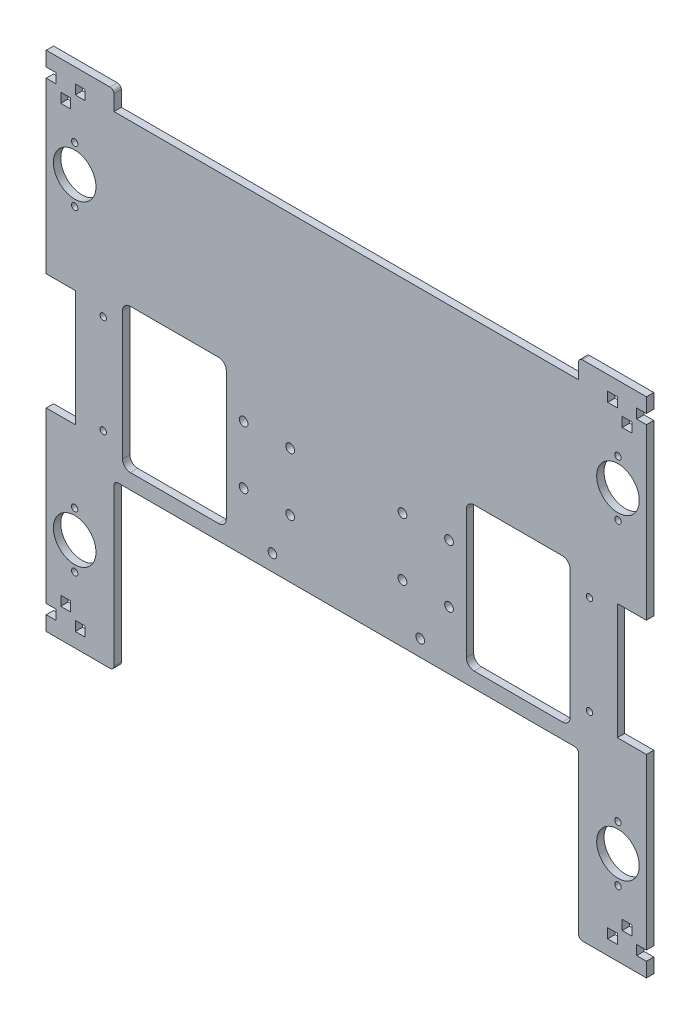
SolidWorks part; units mm, degrees
ref_plane "Front Plane" through (0, 0, 0) normal (0, 0, 1) x (1, 0, 0)
ref_plane "Top Plane" through (0, 0, 0) normal (0, 1, 0) x (1, 0, 0)
ref_plane "Right Plane" through (0, 0, 0) normal (1, 0, 0) x (0, 0, -1)
ref_plane "Plane1" through (0, 150, 0) normal (0, 1, 0) x (1, 0, 0)
ref_plane "Plane2" through (0, -150, 0) normal (0, 1, 0) x (1, 0, 0)
ref_plane "Plane3" through (150, 0, 0) normal (1, 0, 0) x (0, 0, -1)
ref_plane "Plane4" through (-150, 0, 0) normal (1, 0, 0) x (0, 0, -1)
sketch "Sketch2" plane through (0, 0, 0) normal (0, 0, 1) x (1, 0, 0)
  line L0 (0, -10.2) -> (0, 50.0764) construction
  line L5 (-53.06, 39.945) -> (-53.06, 10.055) construction
  line L23 (-155, 155) -> (-122, 155)
  line L24 (139.6652, 116) -> (168.3348, 116) construction
  line L31 (-155, -105) -> (-122, -105)
  line L40 (-152.1866, -81.0661) -> (-123.5266, -81.0661) construction
  line L42 (-120, 153) -> (-120, 145.0725)
  line L43 (-120, 145.0725) -> (120, 145.0725)
  line L47 (-66, 62.1714) -> (-111.5977, 62.1714)
  line L48 (66, 62.1714) -> (111.5977, 62.1714)
  line L49 (62, 58.1714) -> (62, -8.1714)
  line L50 (66, -12.1714) -> (111.5977, -12.1714)
  line L51 (115.5977, 58.1714) -> (115.5977, -8.1714)
  line L52 (62, 62.1714) -> (115.5977, -12.1714) construction
  line L53 (62, -12.1714) -> (115.5977, 62.1714) construction
  line L54 (-62, 58.1714) -> (-62, -8.1714)
  line L55 (-66, -12.1714) -> (-111.5977, -12.1714)
  line L56 (-115.5977, 58.1714) -> (-115.5977, -8.1714)
  line L57 (177.1787, -66.0847) -> (177.1787, 11.9153) construction
  line L66 (-155, -97.5) -> (-155, -105)
  line L70 (-125.5977, 50.5) -> (-125.5977, -0.5) construction
  line L73 (-155, 155) -> (-155, 147.5)
  line L74 (162.5, 25) -> (139.6652, 25) construction
  line L75 (-120, -103) -> (-120, -22)
  line L76 (-118, -20) -> (118, -20)
  line L79 (-155, -5) -> (-155, -92.5)
  line L80 (-155, -5) -> (-140, -5)
  line L82 (-155, 55) -> (-140, 55)
  line L83 (-140, -5) -> (-140, 55)
  line L84 (-145.4163, 25) -> (-140, 55) construction
  line L85 (-145.4163, 25) -> (-140, -5) construction
  line L88 (145.4163, 25) -> (140, -5) construction
  line L89 (145.4163, 25) -> (140, 55) construction
  line L90 (125.5977, 50.5) -> (125.5977, -0.5) construction
  line L91 (140, -5) -> (140, 55)
  line L92 (155, 55) -> (140, 55)
  line L93 (155, -5) -> (140, -5)
  line L94 (155, -5) -> (155, -92.5)
  line L95 (155, 155) -> (155, 147.5)
  line L96 (120, -103) -> (120, -22)
  line L97 (155, -105) -> (122, -105)
  line L98 (155, 155) -> (122, 155)
  line L99 (120, 153) -> (120, 145.0725)
  line L100 (-142.5, -90) -> (-147.5, -90)
  line L101 (-142.5, -90) -> (-142.5, -85)
  line L102 (-142.5, -85) -> (-147.5, -85)
  line L103 (-147.5, -90) -> (-147.5, -85)
  line L104 (-155, -92.5) -> (-150, -92.5)
  line L106 (-155, -97.5) -> (-150, -97.5)
  line L107 (-150, -92.5) -> (-150, -97.5)
  line L108 (-140, -92.5) -> (-135, -92.5)
  line L109 (-140, -92.5) -> (-140, -97.5)
  line L110 (-140, -97.5) -> (-135, -97.5)
  line L111 (-135, -92.5) -> (-135, -97.5)
  line L112 (135, -92.5) -> (135, -97.5)
  line L113 (140, -97.5) -> (135, -97.5)
  line L114 (140, -92.5) -> (140, -97.5)
  line L115 (140, -92.5) -> (135, -92.5)
  line L116 (150, -92.5) -> (150, -97.5)
  line L117 (155, -97.5) -> (150, -97.5)
  line L118 (155, -92.5) -> (150, -92.5)
  line L119 (147.5, -90) -> (147.5, -85)
  line L120 (142.5, -85) -> (147.5, -85)
  line L121 (142.5, -90) -> (142.5, -85)
  line L122 (142.5, -90) -> (147.5, -90)
  line L123 (-135, 142.5) -> (-135, 147.5)
  line L124 (-140, 147.5) -> (-135, 147.5)
  line L125 (-140, 142.5) -> (-140, 147.5)
  line L126 (-140, 142.5) -> (-135, 142.5)
  line L127 (-150, 142.5) -> (-150, 147.5)
  line L128 (-155, 147.5) -> (-150, 147.5)
  line L129 (-155, 142.5) -> (-150, 142.5)
  line L130 (-147.5, 140) -> (-147.5, 135)
  line L131 (-142.5, 135) -> (-147.5, 135)
  line L132 (-142.5, 140) -> (-142.5, 135)
  line L133 (-142.5, 140) -> (-147.5, 140)
  line L134 (142.5, 140) -> (147.5, 140)
  line L135 (142.5, 140) -> (142.5, 135)
  line L136 (142.5, 135) -> (147.5, 135)
  line L137 (147.5, 140) -> (147.5, 135)
  line L138 (155, 142.5) -> (150, 142.5)
  line L139 (155, 147.5) -> (150, 147.5)
  line L140 (150, 142.5) -> (150, 147.5)
  line L141 (140, 142.5) -> (135, 142.5)
  line L142 (140, 142.5) -> (140, 147.5)
  line L143 (140, 147.5) -> (135, 147.5)
  line L144 (135, 142.5) -> (135, 147.5)
  line L145 (155, -97.5) -> (155, -105)
  line L146 (155, 142.5) -> (155, 55)
  line L147 (-155, 142.5) -> (-155, 55)
  circle A1 centre (-140.3098, 121.0768) radius 1.65
  circle A2 centre (-140.3098, 92.4072) radius 1.65
  circle A3 centre (140.3098, 121.0768) radius 1.65
  circle A4 centre (140.3098, 92.4072) radius 1.65
  circle A9 centre (140.3098, 106.742) radius 11
  circle A10 centre (-140.3098, 106.742) radius 11
  circle A17 centre (125.5977, -0.5) radius 1.65
  circle A18 centre (125.5977, 50.5) radius 1.65
  circle A19 centre (-125.5977, -0.5) radius 1.65
  circle A20 centre (-125.5977, 50.5) radius 1.65
  circle A27 centre (-29, 10.055) radius 2.25
  circle A32 centre (-29, 39.945) radius 2.25
  circle A33 centre (-53.06, 39.945) radius 2.25
  circle A34 centre (-53.06, 10.055) radius 2.25
  circle A35 centre (53.06, 10.055) radius 2.25
  circle A36 centre (29, 10.055) radius 2.25
  circle A37 centre (29, 39.945) radius 2.25
  circle A38 centre (53.06, 39.945) radius 2.25
  arc A47 (-120, 153) -> (-122, 155) centre (-122, 153) ccw
  arc A48 (62, -8.1714) -> (66, -12.1714) centre (66, -8.1714) ccw
  arc A49 (111.5977, -12.1714) -> (115.5977, -8.1714) centre (111.5977, -8.1714) ccw
  arc A50 (111.5977, 62.1714) -> (115.5977, 58.1714) centre (111.5977, 58.1714) cw
  arc A51 (66, 62.1714) -> (62, 58.1714) centre (66, 58.1714) ccw
  arc A52 (-111.5977, 62.1714) -> (-115.5977, 58.1714) centre (-111.5977, 58.1714) ccw
  arc A53 (-66, 62.1714) -> (-62, 58.1714) centre (-66, 58.1714) cw
  arc A54 (-62, -8.1714) -> (-66, -12.1714) centre (-66, -8.1714) cw
  arc A55 (-111.5977, -12.1714) -> (-115.5977, -8.1714) centre (-111.5977, -8.1714) cw
  circle A68 centre (140.3098, -71.0768) radius 1.65
  circle A69 centre (140.3098, -42.4072) radius 1.65
  circle A70 centre (140.3098, -56.742) radius 11
  circle A71 centre (-140.3098, -56.742) radius 11
  circle A72 centre (-140.3098, -42.4072) radius 1.65
  circle A73 centre (-140.3098, -71.0768) radius 1.65
  arc A76 (-120, -22) -> (-118, -20) centre (-118, -22) cw
  arc A77 (-120, -103) -> (-122, -105) centre (-122, -103) cw
  arc A79 (120, -22) -> (118, -20) centre (118, -22) ccw
  arc A80 (120, -103) -> (122, -105) centre (122, -103) ccw
  arc A81 (120, 153) -> (122, 155) centre (122, 153) cw
  circle A82 centre (38.1799, -11.5638) radius 2.25
  circle A83 centre (-38.1799, -11.5638) radius 2.25
  point P0 (0, 0)
  point P2 (0, 0)
  point P4 (0, 150)
  point P7 (-145.4163, 25)
  point P11 (-125.5977, 25)
  point P12 (88.7989, 25)
  point P23 (-53.06, 25)
  point P24 (0, -20)
  point P33 (-140, 25)
  point P82 (177.1787, -27.0847)
  point P111 (-115.5977, 25)
  point P112 (145.4163, 25)
  point P122 (0, 145.0725)
  point P132 (-62, 25)
  dimension "D3" = 51
  dimension "D7" = 155
  dimension "D8" = 3.3
  dimension "D9" = 120
  dimension "D10" = 22
  dimension "D11" = 74.3428
  dimension "D13" = 53.5977
  dimension "D16" = 62
  dimension "D17" = 15
  dimension "D18" = 60
  dimension "D19" = 3.3
  dimension "D6" = 14.3348
  dimension "D20" = 14.3348
  dimension "D21" = 130
  dimension "D23" = 4.5
  dimension "D24" = 45
  dimension "D25" = 4.5
  dimension "D26" = 4.5
  dimension "D27" = 29.89
  dimension "D29" = 24.06
  dimension "D31" = 4
  dimension "D32" = 130
  dimension "D4" = 3.3
  dimension "D5" = 10
  dimension "D22" = 29.89
  dimension "D28" = 24.06
  dimension "D30" = 29
  dimension "D14" = 2
extrude "Boss-Extrude1" add sketch "Sketch2" along normal blind 3.8
